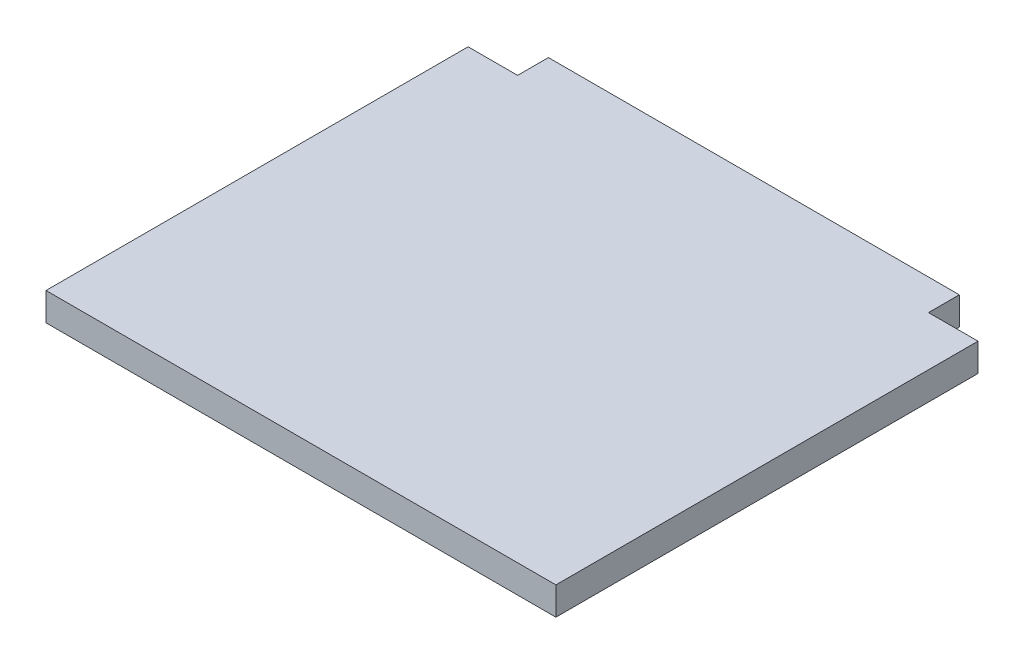
SolidWorks part; units mm, degrees
ref_plane "Front Plane" through (0, 0, 0) normal (0, 0, 1) x (1, 0, 0)
ref_plane "Top Plane" through (0, 0, 0) normal (0, 1, 0) x (1, 0, 0)
ref_plane "Right Plane" through (0, 0, 0) normal (1, 0, 0) x (0, 0, -1)
sketch "Sketch2" plane through (0, 0, 0) normal (0, 1, 0) x (1, 0, 0)
  line L1 (-27.3, 22.6) -> (-22, 22.6)
  line L2 (-27.3, 22.6) -> (-27.3, -22.6)
  line L3 (-27.3, -22.6) -> (27.3, -22.6)
  line L4 (27.3, 22.6) -> (27.3, -22.6)
  line L5 (-27.3, 22.6) -> (27.3, -22.6) construction
  line L6 (-27.3, -22.6) -> (27.3, 22.6) construction
  line L7 (-22, 25.9) -> (22, 25.9)
  line L8 (-22, 25.9) -> (-22, 22.6)
  line L9 (22, 25.9) -> (22, 22.6)
  line L11 (22, 22.6) -> (27.3, 22.6)
  point P0 (0, 0)
  point P6 (27.3, 0)
  point P12 (0, 25.9)
  dimension "D1" = 54.6
  dimension "D2" = 45.2
  dimension "D3" = 3.3
  dimension "D4" = 44
extrude "Boss-Extrude1" add sketch "Sketch2" against normal blind 3
